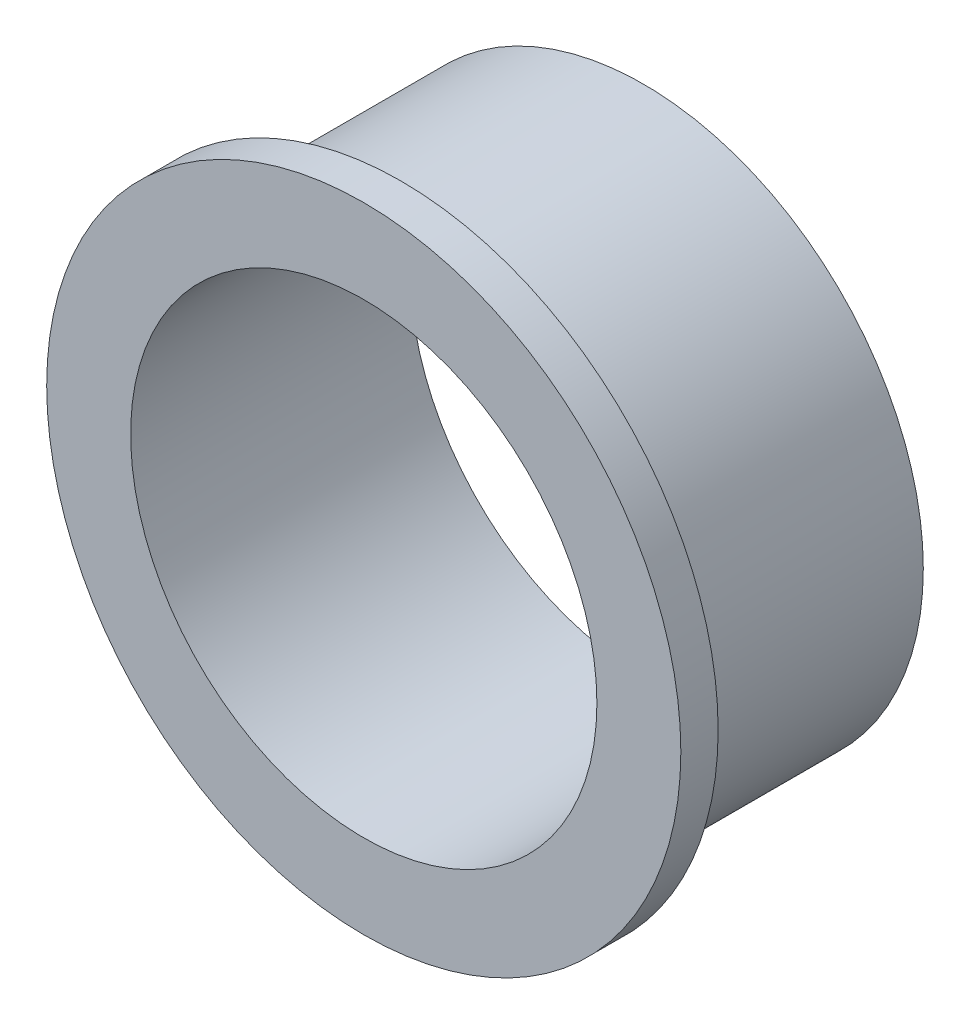
SolidWorks part; units mm, degrees
material "Brass"
ref_plane "Front Plane" through (0, 0, 0) normal (0, 0, 1) x (1, 0, 0)
ref_plane "Top Plane" through (0, 0, 0) normal (0, 1, 0) x (1, 0, 0)
ref_plane "Right Plane" through (0, 0, 0) normal (1, 0, 0) x (0, 0, -1)
sketch "Sketch1" plane through (0, 0, 0) normal (0, 0, 1) x (1, 0, 0)
  circle A0 centre (0, 0) radius 12.5
  circle A1 centre (0, 0) radius 15
  dimension "D1" = 30
  dimension "D2" = 25
extrude "Boss-Extrude1" add sketch "Sketch1" along normal blind 15
sketch "Sketch3" plane through (0, 0, 15) normal (0, 0, 1) x (1, 0, 0)
  circle A0 centre (0, 0) radius 15
  circle A1 centre (0, 0) radius 17
extrude "Boss-Extrude3" add sketch "Sketch3" against normal blind 2
